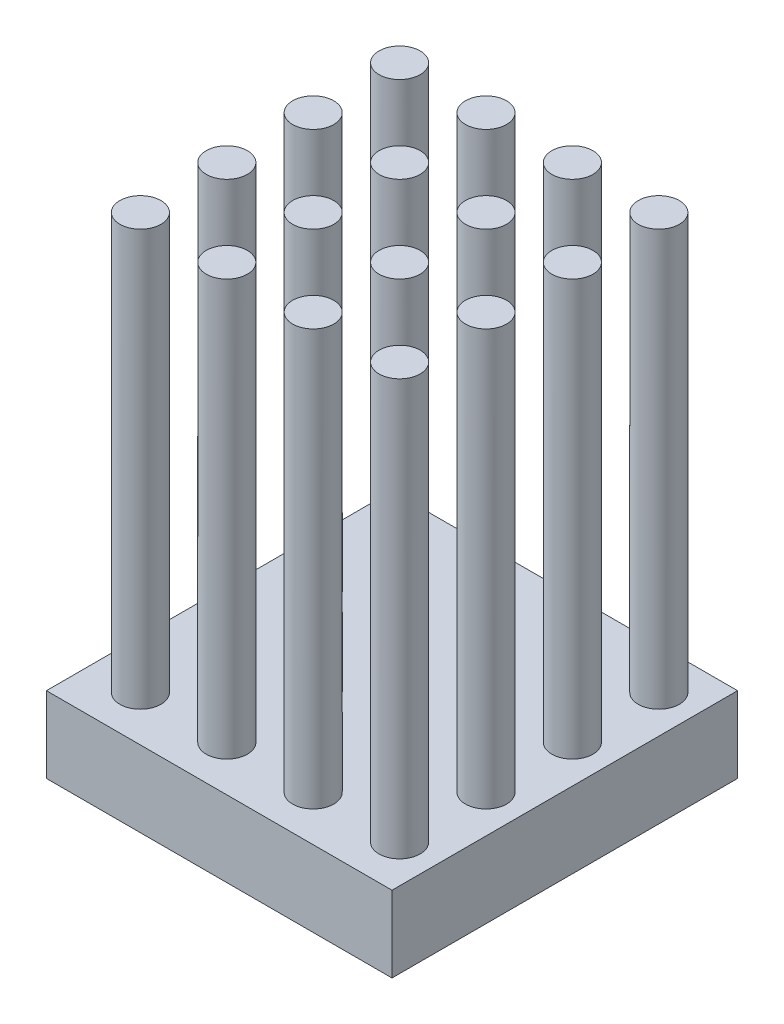
SolidWorks part; units mm, degrees
ref_plane "Front Plane" through (0, 0, 0) normal (0, 0, 1) x (1, 0, 0)
ref_plane "Top Plane" through (0, 0, 0) normal (0, 1, 0) x (1, 0, 0)
ref_plane "Right Plane" through (0, 0, 0) normal (1, 0, 0) x (0, 0, -1)
sketch "Sketch1" plane through (0, 0, 0) normal (0, 1, 0) x (1, 0, 0)
  line L1 (5, 5) -> (-5, 5)
  line L2 (5, 5) -> (5, -5)
  line L3 (5, -5) -> (-5, -5)
  line L4 (-5, 5) -> (-5, -5)
  line L5 (5, 5) -> (-5, -5) construction
  line L6 (5, -5) -> (-5, 5) construction
  point P0 (0, 0)
  dimension "D1" = 10
  dimension "D2" = 10
extrude "Boss-Extrude1" add sketch "Sketch1" along normal blind 2.2
sketch "Sketch2" plane through (0, 2.2, 0) normal (0, 1, 0) x (1, 0, 0)
  line L1 (-5, 5) -> (-5, -5) construction
  line L2 (-5, -5) -> (5, -5) construction
  circle A0 centre (-3.595, -3.685) radius 0.595
  dimension "D2" = 0.72
  dimension "D3" = 1.19
  dimension "D1" = 2
extrude "Boss-Extrude2" add sketch "Sketch2" along normal blind 12.03
pattern_linear "LPattern1" count 4 spacing 2.5 along (1, 0, 0) count 4 spacing 2.5 along (0, 0, -1) of "Boss-Extrude2"
